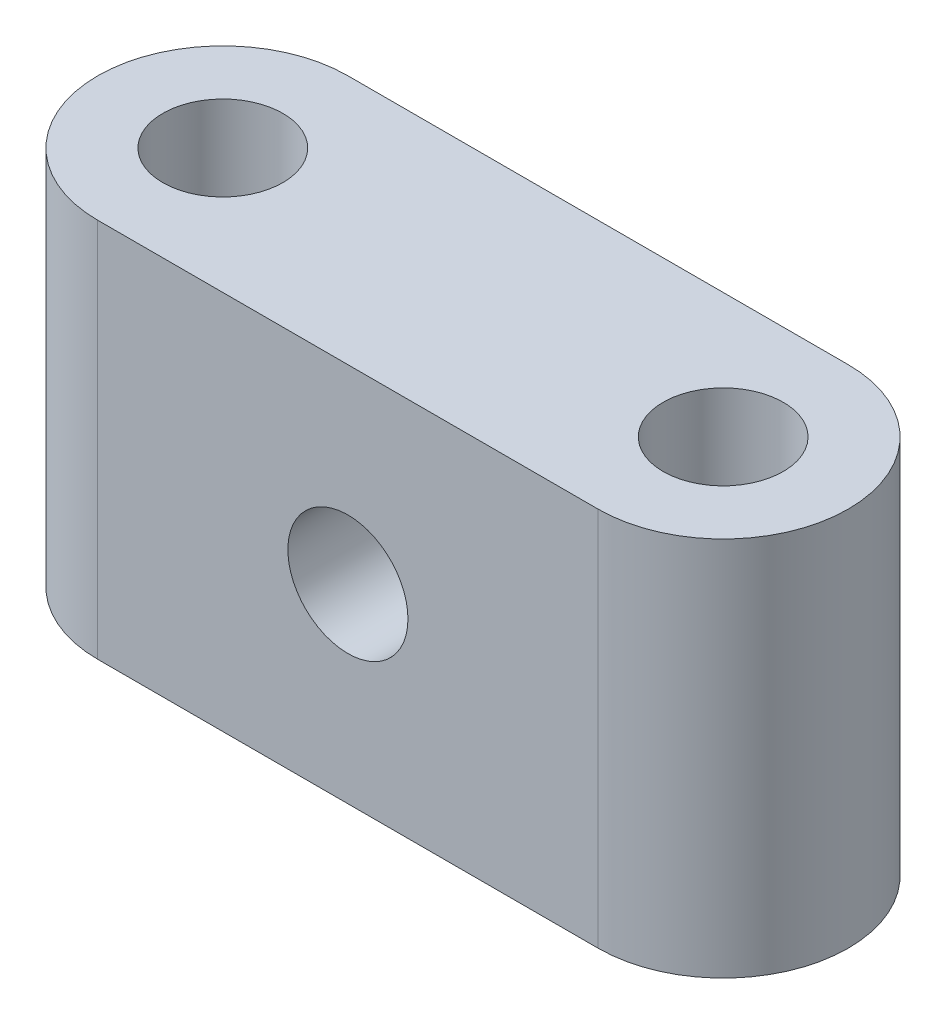
SolidWorks part; units mm, degrees
ref_plane "Front Plane" through (0, 0, 0) normal (0, 0, 1) x (1, 0, 0)
ref_plane "Top Plane" through (0, 0, 0) normal (0, 1, 0) x (1, 0, 0)
ref_plane "Right Plane" through (0, 0, 0) normal (1, 0, 0) x (0, 0, -1)
sketch "Sketch1" plane through (0, 0, 0) normal (0, 1, 0) x (1, 0, 0)
  line L0 (-25, 0) -> (25, 0) construction
  line L1 (-25, 12.5) -> (25, 12.5)
  line L2 (-25, -12.5) -> (25, -12.5)
  arc A0 (-25, 12.5) -> (-25, -12.5) centre (-25, 0) ccw
  arc A1 (25, -12.5) -> (25, 12.5) centre (25, 0) ccw
  circle A2 centre (-25, 0) radius 6
  circle A3 centre (25, 0) radius 6
  point P2 (0, 0)
  dimension "D1" = 12
  dimension "D3" = 12.5
  dimension "D4" = 50
  dimension "D2" = 12.5
extrude "Boss-Extrude1" add sketch "Sketch1" along normal mid plane 38
sketch "Sketch2" plane through (0, 0, 12.5) normal (0, 0, 1) x (1, 0, 0)
  circle A0 centre (0, 0) radius 6
  dimension "D1" = 12
extrude "Cut-Extrude1" cut sketch "Sketch2" against normal blind 12
